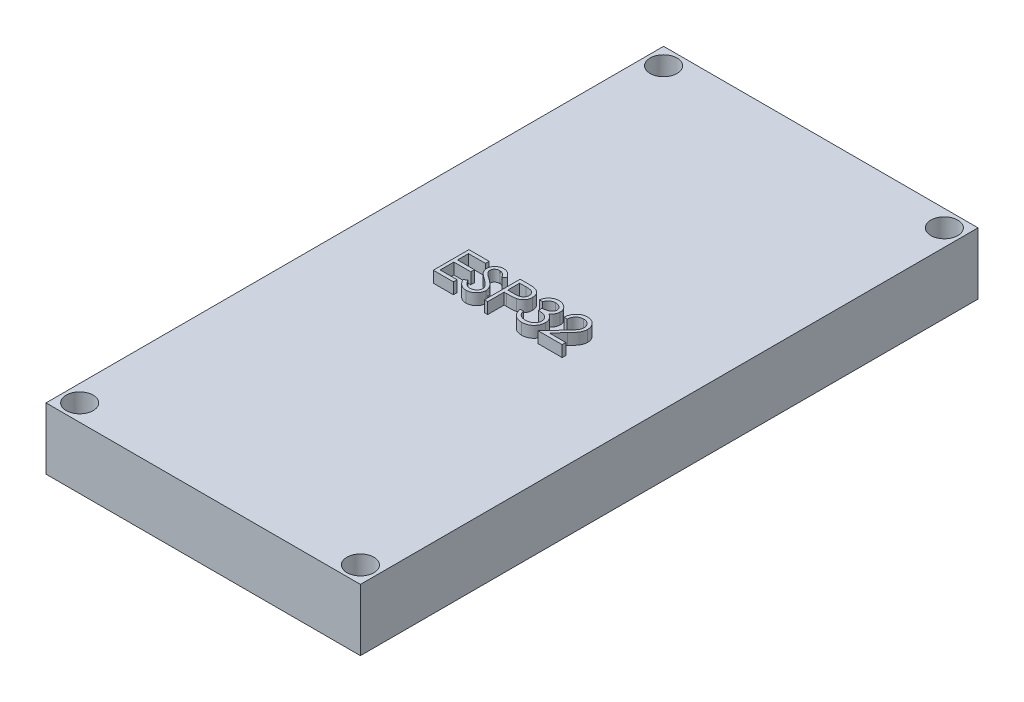
SolidWorks part; units mm, degrees
ref_plane "Front Plane" through (0, 0, 0) normal (0, 0, 1) x (1, 0, 0)
ref_plane "Top Plane" through (0, 0, 0) normal (0, 1, 0) x (1, 0, 0)
ref_plane "Right Plane" through (0, 0, 0) normal (1, 0, 0) x (0, 0, -1)
sketch "Sketch1" plane through (0, 0, 0) normal (0, 1, 0) x (1, 0, 0)
  line L1 (-14, -27.5) -> (14, -27.5)
  line L2 (-14, -27.5) -> (-14, 27.5)
  line L3 (-14, 27.5) -> (14, 27.5)
  line L4 (14, -27.5) -> (14, 27.5)
  line L5 (-14, -27.5) -> (14, 27.5) construction
  line L6 (-14, 27.5) -> (14, -27.5) construction
  circle A0 centre (-12.5, 26) radius 1.2
  circle A1 centre (-12.5, -26) radius 1.2
  circle A2 centre (12.5, -26) radius 1.2
  circle A3 centre (12.5, 26) radius 1.2
  point P0 (0, 0)
  dimension "D3" = 2.4
  dimension "D4" = 1.5
  dimension "D5" = 1.5
  dimension "D1" = 28
  dimension "D2" = 55
  dimension "D6" = 0
  dimension "D7" = 1.5
  dimension "D8" = 0
  dimension "D9" = 1.5
  dimension "D10" = 0
  dimension "D11" = 0
extrude "Boss-Extrude1" add sketch "Sketch1" along normal blind 5.5 contours A2 | A0 | A3 | L2 L3 L4 L1 | A1
sketch "Sketch2" plane through (0, 5.5, 0) normal (0, 1, 0) x (1, 0, 0)
  text T0 "ESP32"
  point P1 (-4.5908, -0.6003)
  point P2 (-6.3918, -1.0241)
  point P3 (0, 0)
extrude "Boss-Extrude2" add sketch "Sketch2" along normal blind 1
